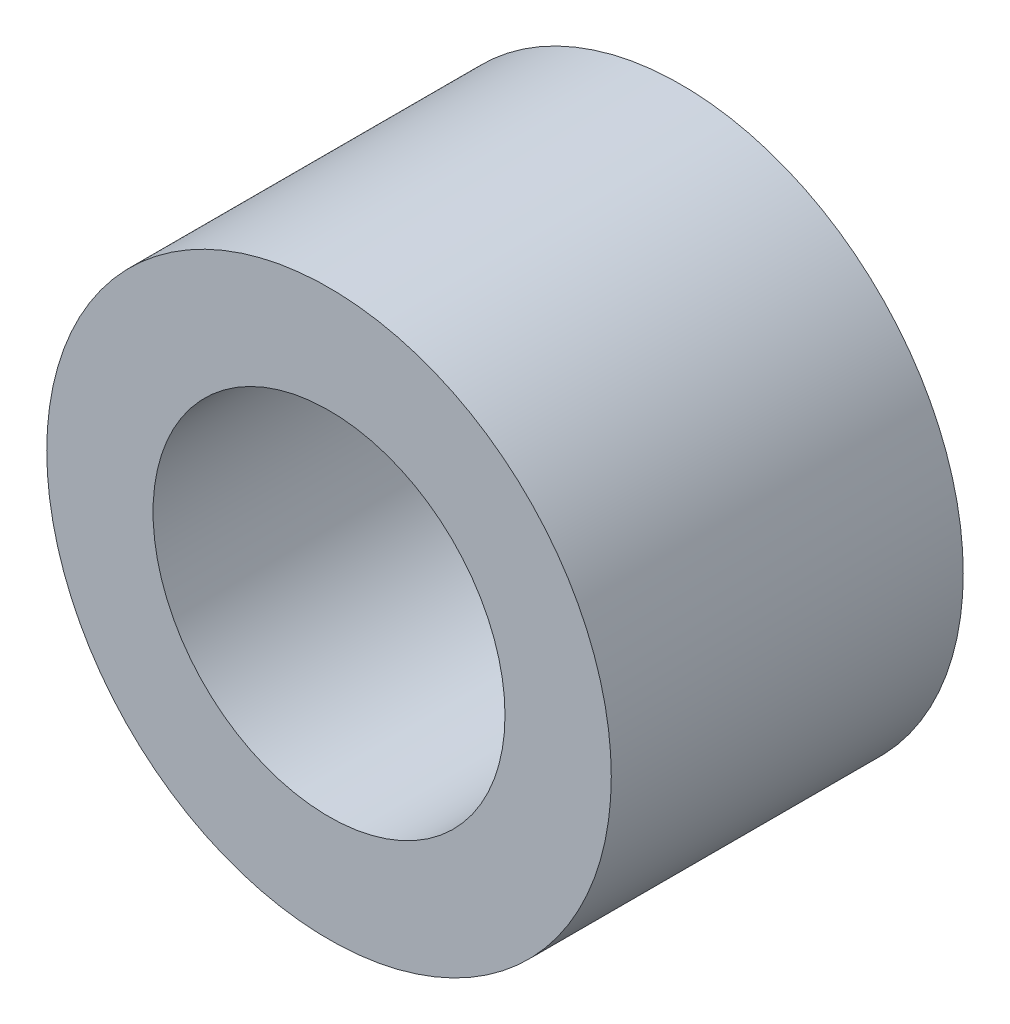
SolidWorks part; units mm, degrees
material "Brass"
ref_plane "Front Plane" through (0, 0, 0) normal (0, 0, 1) x (1, 0, 0)
ref_plane "Top Plane" through (0, 0, 0) normal (0, 1, 0) x (1, 0, 0)
ref_plane "Right Plane" through (0, 0, 0) normal (1, 0, 0) x (0, 0, -1)
sketch "Sketch1" plane through (0, 0, 0) normal (0, 0, 1) x (1, 0, 0)
  circle A0 centre (0, 0) radius 4.01
  circle A1 centre (0, 0) radius 2.5
  dimension "D1" = 8.02
  dimension "ID" = 5
extrude "Extrude1" add sketch "Sketch1" along normal mid plane 5
sketch "Sketch2" plane through (0, 0, 0) normal (1, 0, 0) x (0, 0, -1)
  line L0 (-2.5, -2.5) -> (2.5, -2.5) construction
  line L3 (2.5, 2.5) -> (-2.5, 2.5) construction
  line L5 (-2.5, -2.5) -> (2.5, -2.5)
  line L6 (2.5, 2.5) -> (-2.5, 2.5)
sketch "Sketch4" plane through (0, 0, 2.5) normal (0, 0, 1) x (1, 0, 0)
  line L0 (0, 0) -> (-1.7678, 1.7678)
  line L1 (0, -5.5) -> (0, 5.5) construction
  circle A0 centre (0, 0) radius 2.5 construction
  dimension "D1" = 45
